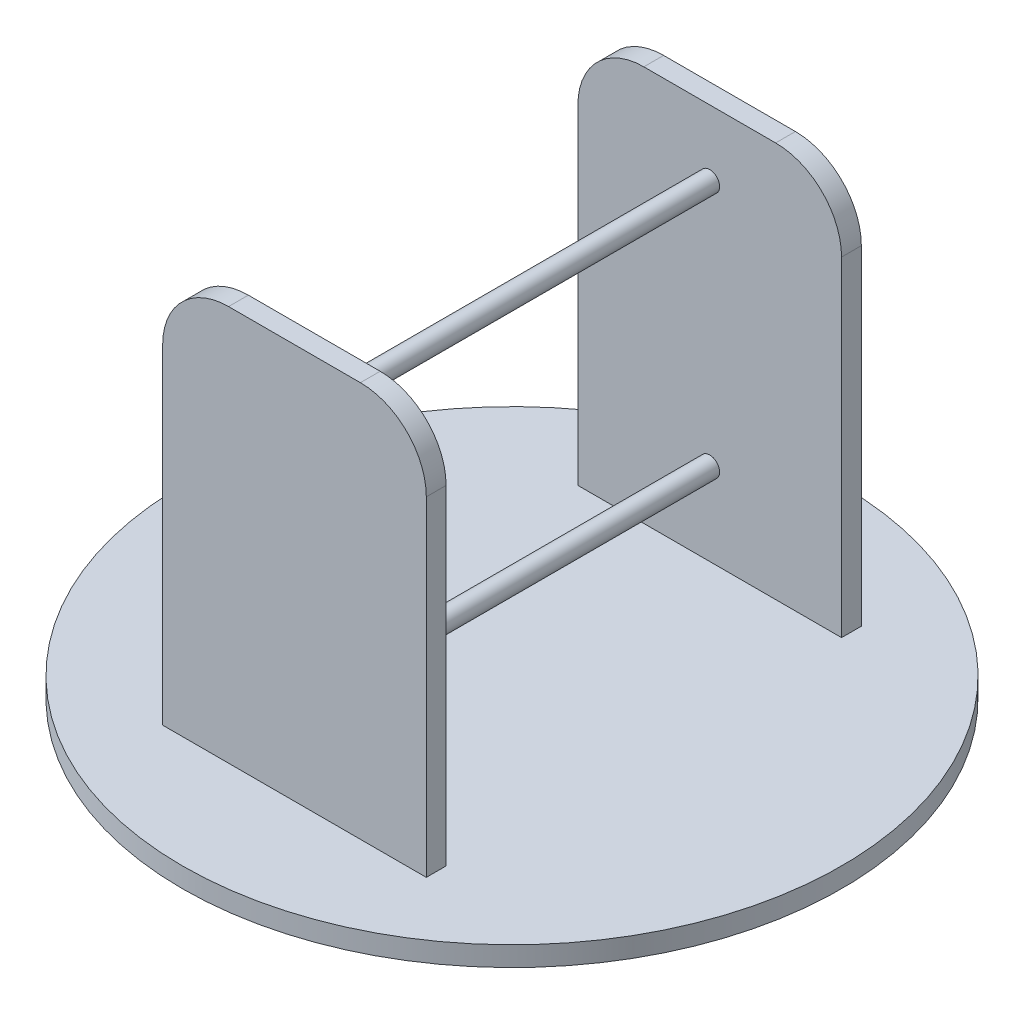
SolidWorks part; units mm, degrees
material "ENPH 253 Hardboard"
ref_plane "Front Plane" through (0, 0, 0) normal (0, 0, 1) x (1, 0, 0)
ref_plane "Top Plane" through (0, 0, 0) normal (0, 1, 0) x (1, 0, 0)
ref_plane "Right Plane" through (0, 0, 0) normal (1, 0, 0) x (0, 0, -1)
sketch "Sketch1" plane through (0, 0, 0) normal (0, 1, 0) x (1, 0, 0)
  circle A0 centre (0, 0) radius 50
  dimension "D1" = 100
extrude "Boss-Extrude1" add sketch "Sketch1" along normal blind 3
sketch "Sketch2" plane through (0, 0, 0) normal (0, -1, 0) x (-1, 0, 0)
  circle A0 centre (0, 0) radius 15
  dimension "D1" = 30
extrude "Boss-Extrude2" [suppressed] add sketch "Sketch2" along normal blind 50
sketch "Sketch3" plane through (0, 3, 0) normal (0, 1, 0) x (1, 0, 0)
  line L1 (-20, -33) -> (20, -33)
  line L2 (-20, -33) -> (-20, -30)
  line L3 (-20, -30) -> (20, -30)
  line L4 (20, -33) -> (20, -30)
  line L5 (-20, 30) -> (20, 30)
  line L6 (-20, 30) -> (-20, 33)
  line L7 (-20, 33) -> (20, 33)
  line L8 (20, 30) -> (20, 33)
  dimension "D1" = 40
  dimension "D2" = 3
  dimension "D5" = 30
  dimension "D6" = 30
  dimension "D7" = 20
  dimension "D3" = 20
extrude "Boss-Extrude3" add sketch "Sketch3" along normal blind 60
sketch "Sketch4" plane through (0, 0, 33) normal (0, 0, 1) x (1, 0, 0)
  line L2 (-20, 3) -> (20, 3) construction
  circle A0 centre (0, 53) radius 1.5
  circle A1 centre (0, 53) radius 30 construction
  circle A2 centre (0, 15.5) radius 1.5
  circle A3 centre (0, 15.5) radius 7.5 construction
  dimension "D1" = 3
  dimension "D2" = 50
  dimension "D3" = 60
  dimension "D4" = 3
  dimension "D5" = 15
extrude "Boss-Extrude4" add sketch "Sketch4" against normal up to surface (63 mm away) contours A0 | A2 up to face at (0, 33, -30)
fillet "Fillet1" radius 10 4 edges at (-20, 63, 31.5) (-20, 63, -31.5) (20, 63, -31.5) (20, 63, 31.5)
equation "\"D7@Sketch3\"=\"D1@Sketch3\"/2"
equation "\"D3@Sketch3\"=\"D7@Sketch3\""
